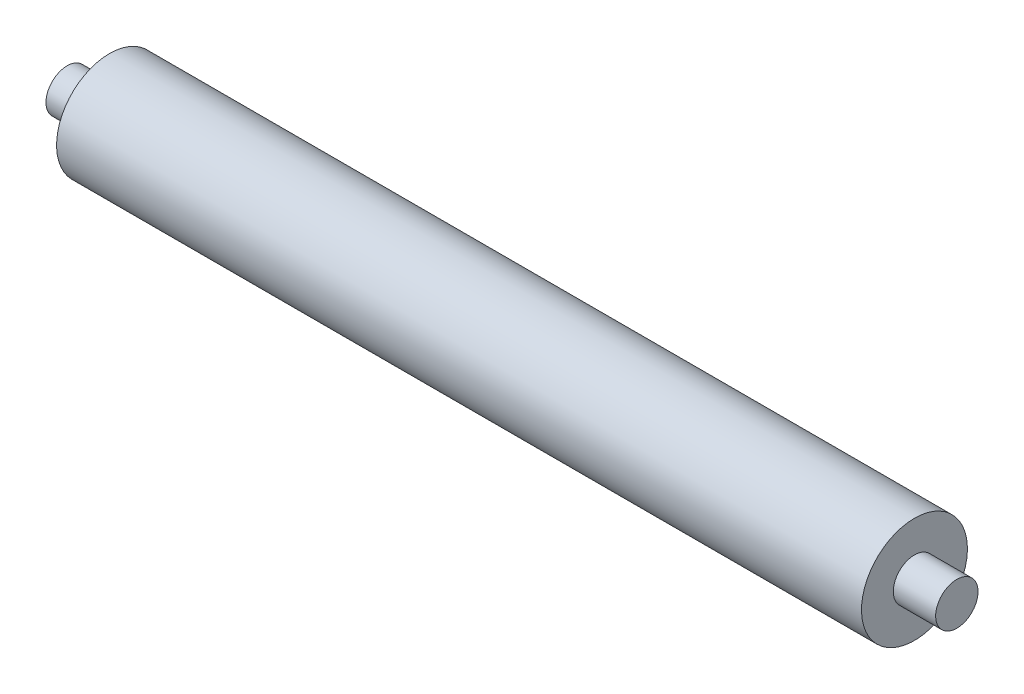
SolidWorks part; units mm, degrees
ref_plane "Front Plane" through (0, 0, 0) normal (0, 0, 1) x (1, 0, 0)
ref_plane "Top Plane" through (0, 0, 0) normal (0, 1, 0) x (1, 0, 0)
ref_plane "Right Plane" through (0, 0, 0) normal (1, 0, 0) x (0, 0, -1)
sketch "Sketch2" plane through (0, 0, 0) normal (0, 0, 1) x (1, 0, 0)
  line L0 (0, 0) -> (0, 5)
  line L1 (0, 5) -> (10, 5)
  line L2 (10, 5) -> (10, 12.5)
  line L3 (10, 12.5) -> (200, 12.5)
  line L4 (200, 12.5) -> (200, 5)
  line L5 (200, 5) -> (210, 5)
  line L6 (210, 5) -> (210, 0)
  line L7 (210, 0) -> (0, 0)
  dimension "D1" = 5
  dimension "D2" = 10
  dimension "D3" = 10
  dimension "D4" = 190
  dimension "D5" = 12.5
revolve "Revolve1" add sketch "Sketch2" angle 360 about L7
